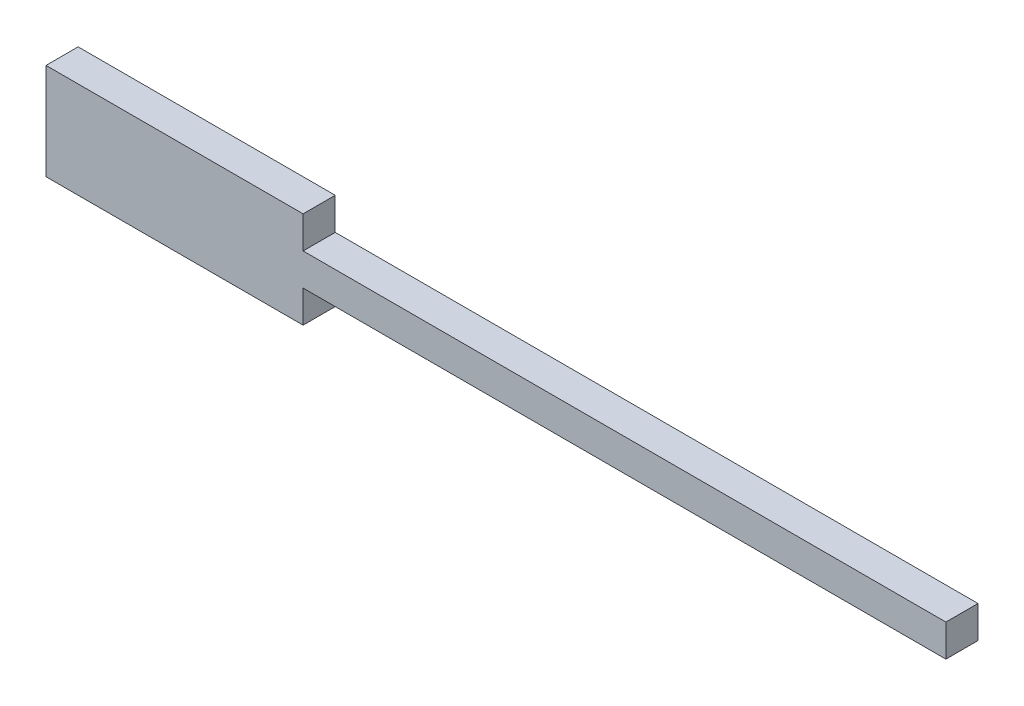
SolidWorks part; units mm, degrees
ref_plane "Front" through (0, 0, 0) normal (0, 0, 1) x (1, 0, 0)
ref_plane "Top" through (0, 0, 0) normal (0, 1, 0) x (1, 0, 0)
ref_plane "Right" through (0, 0, 0) normal (1, 0, 0) x (0, 0, -1)
sketch "Sketch1" plane through (0, 0, 0) normal (0, 0, 1) x (1, 0, 0)
  line L0 (-54.0935, 7.5) -> (85.9065, 7.5) construction
  line L1 (-54.0935, 0) -> (-14.0935, 0)
  line L2 (-54.0935, 0) -> (-54.0935, 15)
  line L3 (-54.0935, 15) -> (-14.0935, 15)
  line L4 (-14.0935, 15) -> (-14.0935, 10)
  line L5 (-14.0935, 5) -> (-14.0935, 0)
  line L6 (-14.0935, 10) -> (85.9065, 10)
  line L8 (-14.0935, 5) -> (85.9065, 5)
  line L9 (85.9065, 10) -> (85.9065, 5)
  point P10 (85.9065, 7.5)
  dimension "D1" = 15
  dimension "D2" = 5
  dimension "D3" = 40
  dimension "D4" = 100
extrude "Boss-Extrude1" add sketch "Sketch1" along normal blind 5
